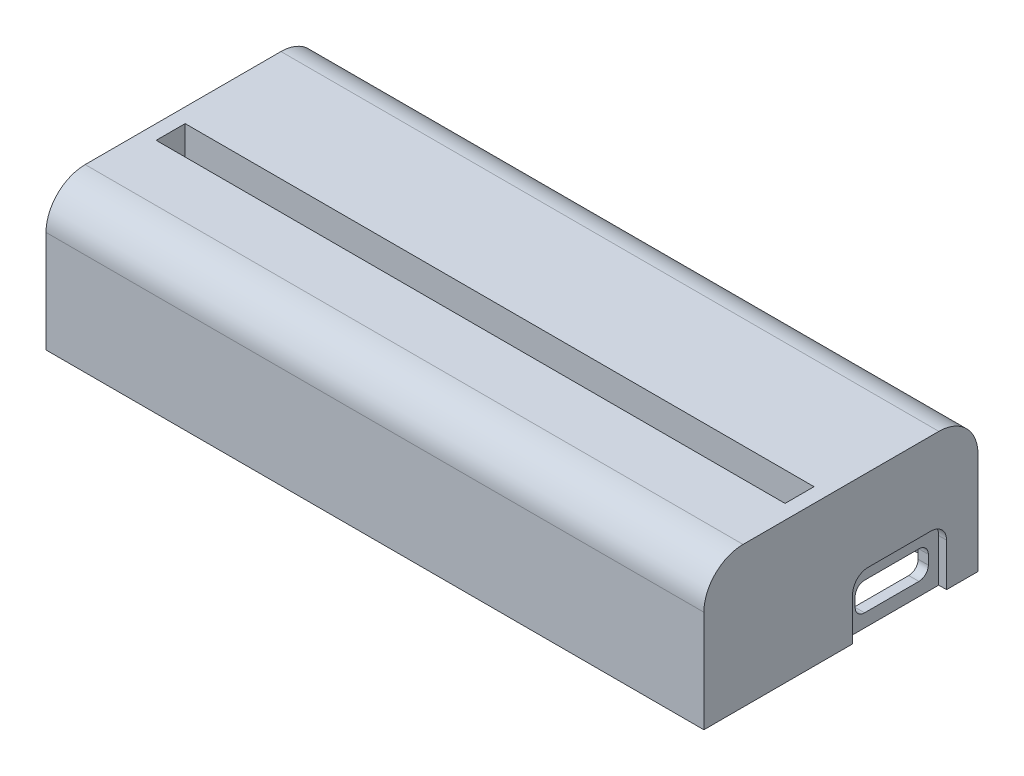
SolidWorks part; units mm, degrees
ref_plane "Front Plane" through (0, 0, 0) normal (0, 0, 1) x (1, 0, 0)
ref_plane "Top Plane" through (0, 0, 0) normal (0, 1, 0) x (1, 0, 0)
ref_plane "Right Plane" through (0, 0, 0) normal (1, 0, 0) x (0, 0, -1)
sketch "Sketch1" plane through (0, 0, 0) normal (0, 1, 0) x (1, 0, 0)
  line L1 (-34, -17.5) -> (34, -17.5)
  line L2 (-34, -17.5) -> (-34, 17.5)
  line L3 (-34, 17.5) -> (34, 17.5)
  line L4 (34, -17.5) -> (34, 17.5)
  line L5 (-34, -17.5) -> (34, 17.5) construction
  line L6 (-34, 17.5) -> (34, -17.5) construction
  point P0 (0, 0)
  dimension "D1" = 35
  dimension "D2" = 68
extrude "Boss-Extrude1" add sketch "Sketch1" along normal blind 18
sketch "Sketch3" plane through (0, 0, 0) normal (0, -1, 0) x (1, 0, 0)
  line L14 (31.7, -15.7) -> (31.7, 12.64)
  line L15 (-25.85, -15.7) -> (31.7, -15.7)
  line L16 (-25.85, 12.64) -> (-25.85, -15.7)
  line L17 (31.7, 12.64) -> (-25.85, 12.64)
  line L18 (31.7, -15.7) -> (31.7, 12.64)
  line L19 (-25.85, -15.7) -> (31.7, -15.7)
  line L20 (-25.85, 12.64) -> (-25.85, 7.67)
  line L21 (31.7, 12.64) -> (-25.85, 12.64)
  line L24 (-25.85, -10.73) -> (-25.85, -15.7)
  line L27 (-24.85, -10.73) -> (-32.09, -10.73)
  line L28 (-32.09, -10.73) -> (-32.09, 7.67)
  line L29 (-32.09, 7.67) -> (-24.85, 7.67)
  line L30 (-25.85, -10.73) -> (-32.09, -10.73)
  line L31 (-32.09, -10.73) -> (-32.09, 7.67)
  line L32 (-32.09, 7.67) -> (-25.85, 7.67)
  dimension "D1" = 0.2
  dimension "D2" = 0.2
extrude "Cut-Extrude1" cut sketch "Sketch3" against normal blind 5.28
sketch "Sketch4" plane through (0, 5.28, 0) normal (0, -1, 0) x (1, 0, 0)
  line L0 (31.7, -15.7) -> (31.7, 12.64) construction
  line L1 (-25.85, 12.64) -> (31.7, 12.64)
  line L2 (-25.85, 12.64) -> (-25.85, 10.84)
  line L3 (-25.85, 10.84) -> (31.7, 10.84)
  line L4 (31.7, 12.64) -> (31.7, 10.84)
  line L6 (31.7, -15.7) -> (-25.85, -15.7)
  line L7 (31.7, -15.7) -> (31.7, -13.9)
  line L8 (31.7, -13.9) -> (-25.85, -13.9)
  line L9 (-25.85, -15.7) -> (-25.85, -13.9)
  dimension "D1" = 1.8
  dimension "D2" = 1.8
extrude "Boss-Extrude2" add sketch "Sketch4" along normal blind 3.46
sketch "Sketch5" plane through (0, 0, 0) normal (0, -1, 0) x (1, 0, 0)
  line L0 (-34, 17.5) -> (34, 17.5) construction
  line L1 (-34, -17.5) -> (-34, 17.5) construction
  line L2 (34, -17.5) -> (-34, -17.5) construction
  line L3 (34, 17.5) -> (34, -17.5) construction
  circle A0 centre (29.5, 14.5) radius 2.5
  circle A1 centre (-30.5, -14) radius 2.5
  circle A2 centre (29.5, 14.5) radius 1.5
  point P4 (29.6023, 14.5)
  line M6 (-25.85, 12.64) -> (31.7, 12.64)
  dimension "D1" = 5
  dimension "D2" = 5
  dimension "D4" = 3
  dimension "D6" = 3.5
  dimension "D3" = 3
  dimension "D5" = 3.5
  dimension "D7" = 4.5
extrude "Cut-Extrude2" cut sketch "Sketch5" against normal blind 6 contours A2 | A0 A2 M6 | A1
sketch "Sketch6" plane through (-34, 0, 0) normal (-1, 0, 0) x (0, 0, 1)
  line L1 (-17.5, 18) -> (17.5, 18)
  line L2 (-17.5, 18) -> (-17.5, 0)
  line L3 (-17.5, 0) -> (17.5, 0)
  line L4 (17.5, 18) -> (17.5, 0)
extrude "Boss-Extrude3" add sketch "Sketch6" along normal blind 16
sketch "Sketch8" plane through (34, 0, 0) normal (1, 0, 0) x (0, 0, -1)
  line L29 (2.8162, 4.08) -> (2.8162, 2.88)
  line L30 (4.0162, 1.68) -> (10.9562, 1.68)
  line L31 (12.1562, 2.88) -> (12.1562, 4.08)
  line L32 (10.9562, 5.28) -> (4.0162, 5.28)
  line L33 (2.8162, 4.08) -> (2.8162, 2.88)
  line L34 (4.0162, 1.68) -> (10.9562, 1.68)
  line L35 (12.1562, 2.88) -> (12.1562, 4.08)
  line L36 (10.9562, 5.28) -> (4.0162, 5.28)
  arc A20 (4.0162, 5.28) -> (2.8162, 4.08) centre (4.0162, 4.08) ccw
  arc A21 (2.8162, 2.88) -> (4.0162, 1.68) centre (4.0162, 2.88) ccw
  arc A22 (10.9562, 1.68) -> (12.1562, 2.88) centre (10.9562, 2.88) ccw
  arc A23 (12.1562, 4.08) -> (10.9562, 5.28) centre (10.9562, 4.08) ccw
  arc A24 (4.0162, 5.28) -> (2.8162, 4.08) centre (4.0162, 4.08) ccw
  arc A25 (2.8162, 2.88) -> (4.0162, 1.68) centre (4.0162, 2.88) ccw
  arc A26 (10.9562, 1.68) -> (12.1562, 2.88) centre (10.9562, 2.88) ccw
  arc A27 (12.1562, 4.08) -> (10.9562, 5.28) centre (10.9562, 4.08) ccw
  dimension "D1" = 0.2
extrude "Cut-Extrude3" cut sketch "Sketch8" against normal blind 3
sketch "Sketch9" plane through (0, 18, 0) normal (0, 1, 0) x (1, 0, 0)
  line L14 (-48.15, -1.5847) -> (-48.15, -5.2847)
  line L15 (-48.15, -5.2847) -> (32.15, -5.2847)
  line L16 (32.15, -5.2847) -> (32.15, -1.5847)
  line L17 (32.15, -1.5847) -> (-48.15, -1.5847)
  line L18 (-48.15, -1.5847) -> (-48.15, -5.2847)
  line L19 (-48.15, -5.2847) -> (32.15, -5.2847)
  line L20 (32.15, -5.2847) -> (32.15, -1.5847)
  line L21 (32.15, -1.5847) -> (-48.15, -1.5847)
  dimension "D1" = 0.15
extrude "Cut-Extrude4" cut sketch "Sketch9" against normal blind 20 contours L20 L21 L18 L19
sketch "Sketch10" plane through (34, 0, 0) normal (1, 0, 0) x (0, 0, -1)
  line L5 (12.1562, 2.88) -> (12.1562, 4.08) construction
  line L14 (2.8162, 4.08) -> (2.8162, 2.88) construction
  line L22 (2.8162, 3.48) -> (12.1562, 3.48) construction
  line L24 (1.4862, -0.52) -> (13.4862, -0.52)
  line L25 (1.4862, -0.52) -> (1.4862, 7.48)
  line L26 (1.4862, 7.48) -> (13.4862, 7.48)
  line L27 (13.4862, -0.52) -> (13.4862, 7.48)
  line L28 (1.4862, -0.52) -> (13.4862, 7.48) construction
  line L29 (1.4862, 7.48) -> (13.4862, -0.52) construction
  point P0 (7.4862, 3.48)
  dimension "D1" = 12
  dimension "D2" = 8
extrude "Cut-Extrude5" cut sketch "Sketch10" against normal blind 1
fillet "Fillet1" radius 2 2 edges at (33.5, 7.48, -1.4862) (33.5, 7.48, -13.4862)
fillet "Fillet2" radius 5 2 edges at (-8, 18, -17.5) (-8, 18, 17.5)
